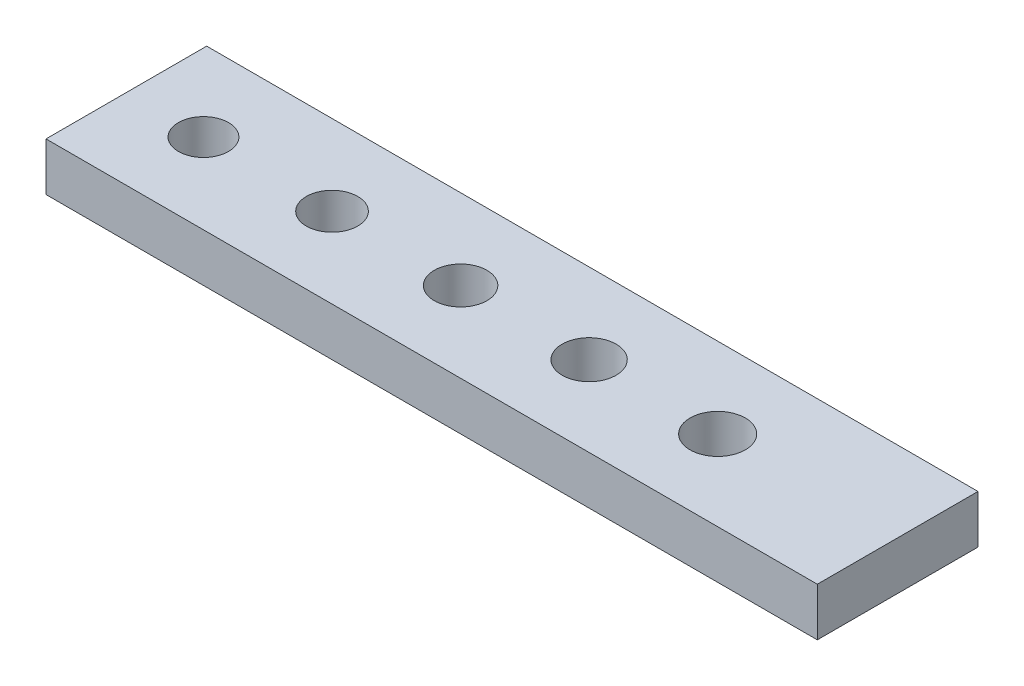
SolidWorks part; units mm, degrees
ref_plane "Front Plane" through (0, 0, 0) normal (0, 0, 1) x (1, 0, 0)
ref_plane "Top Plane" through (0, 0, 0) normal (0, 1, 0) x (1, 0, 0)
ref_plane "Right Plane" through (0, 0, 0) normal (1, 0, 0) x (0, 0, -1)
sketch "Sketch1" plane through (0, 0, 0) normal (0, 1, 0) x (1, 0, 0)
  line L0 (-30.48, -3.175) -> (0, -3.175) construction
  line L1 (0, 0) -> (-30.48, 0)
  line L2 (0, 0) -> (0, -6.35)
  line L3 (0, -6.35) -> (-30.48, -6.35)
  line L4 (-30.48, 0) -> (-30.48, -6.35)
  circle A0 centre (-27.432, -3.175) radius 0.9906
  circle A1 centre (-22.352, -3.175) radius 1.016
  circle A2 centre (-17.272, -3.175) radius 1.0414
  circle A3 centre (-12.192, -3.175) radius 1.0668
  circle A4 centre (-7.112, -3.175) radius 1.0922
  point P12 (-19.7107, -3.81)
  point P13 (-25.0995, -3.81)
  point P14 (-14.5434, -3.81)
  point P15 (0, 0)
  point P22 (-27.4617, -1.8725)
  point P23 (-19.9322, -4.3085)
  dimension "D4" = 2.0828
  dimension "D1" = 1.9812
  dimension "D3" = 2.032
  dimension "D5" = 2.1336
  dimension "D6" = 2.1844
  dimension "D2" = 6.35
  dimension "D7" = 3.048
  dimension "D8" = 5.08
  dimension "D9" = 5.08
  dimension "D10" = 5.08
  dimension "D11" = 5.08
  dimension "D12" = 30.48
extrude "Boss-Extrude1" add sketch "Sketch1" along normal blind 1.905
